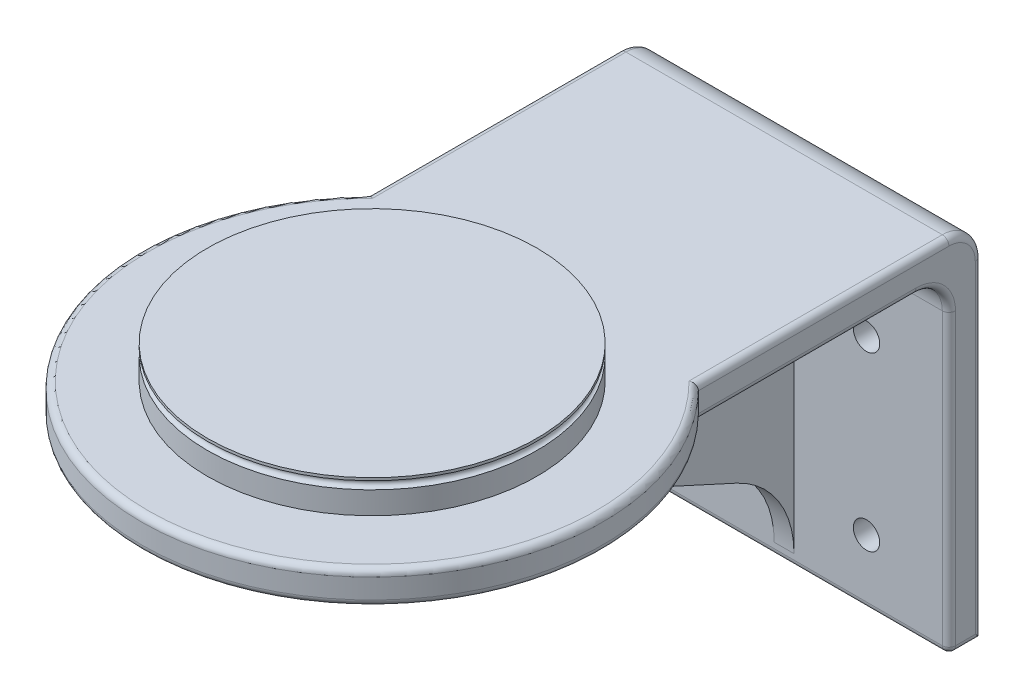
SolidWorks part; units mm, degrees
ref_plane "Front Plane" through (0, 0, 0) normal (0, 0, 1) x (1, 0, 0)
ref_plane "Top Plane" through (0, 0, 0) normal (0, 1, 0) x (1, 0, 0)
ref_plane "Right Plane" through (0, 0, 0) normal (1, 0, 0) x (0, 0, -1)
sketch "Sketch1" plane through (0, 0, 0) normal (1, 0, 0) x (0, 0, -1)
  line L0 (0, 0) -> (-130, 0)
  line L1 (0, 0) -> (0, -50)
  line L2 (-130, 0) -> (-130, 5)
  line L3 (-130, 5) -> (5, 5)
  line L4 (5, 5) -> (5, -50)
  line L5 (5, -50) -> (0, -50)
  dimension "D1" = 130
  dimension "D2" = 50
  dimension "D3" = 5
extrude "Boss-Extrude1" add sketch "Sketch1" along normal blind 50
sketch "Sketch2" plane through (0, 5, 0) normal (0, 1, 0) x (1, 0, 0)
  line L0 (0, 5) -> (50, -130) construction
  circle A0 centre (25, -62.5) radius 25
  dimension "D1" = 50
extrude "Boss-Extrude2" add sketch "Sketch2" along normal blind 5
sketch "Sketch3" plane through (0, 5, 0) normal (0, 1, 0) x (1, 0, 0)
  circle A2 centre (25, -62.5) radius 35
  circle A3 centre (25, -62.5) radius 35
  dimension "D1" = 10
extrude "Boss-Extrude3" add sketch "Sketch3" against normal up to surface (5 mm away) up to face at (25, 0, 65)
ref_plane "Plane1" through (25, 0, 0) normal (1, 0, 0) x (0, 0, -1)
sketch "Sketch4" plane through (25, 0, 0) normal (1, 0, 0) x (0, 0, -1)
  line L0 (-62.5, 10) -> (-62.5, 9) construction
  line L1 (-37.5, 10) -> (-87.5, 10) construction
  line L2 (-62.5, 9) -> (-87.5, 9) construction
  line L3 (-87.5, 10) -> (-87.5, 5) construction
  circle A0 centre (-87.5, 9) radius 0.6
  dimension "D1" = 1.2
  dimension "D2" = 1
sketch "Sketch5" plane through (0, 5, 0) normal (0, 1, 0) x (1, 0, 0)
  line L0 (50, -86.9949) -> (70.537, -86.9949)
  line L1 (70.537, -86.9949) -> (70.537, -135.5769)
  line L2 (70.537, -135.5769) -> (-17.3561, -135.5769)
  line L3 (-17.3561, -135.5769) -> (0, -86.9949)
  line L4 (25, -62.5) -> (25, -87.5) construction
  arc A1 (0, -86.9949) -> (50, -86.9949) centre (25, -62.5) ccw
extrude "Cut-Extrude1" cut sketch "Sketch5" against normal through all
sketch "Sketch7" plane through (25, 0, 0) normal (1, 0, 0) x (0, 0, -1)
  line L0 (0, 0) -> (-84.2622, 0)
  line L1 (-97.5, 0) -> (-38.0051, 0) construction
  line L2 (-84.2622, 0) -> (0, -38.515)
  line L3 (0, 0) -> (0, -50) construction
  line L4 (0, -38.515) -> (0, 0)
extrude "Boss-Extrude5" add sketch "Sketch7" along normal mid plane 3
sketch "Sketch8" plane through (0, 0, 0) normal (0, 0, 1) x (1, 0, 0)
  line L0 (25, -38.515) -> (25, -50) construction
  line L1 (26.5, -38.515) -> (23.5, -38.515) construction
  line L2 (50, -50) -> (0, -50) construction
  line L3 (25, -50) -> (50, -50) construction
  line L4 (25, -50) -> (0, -50) construction
  line L5 (12.5, -50) -> (12.5, 0) construction
  line L6 (23.5, 0) -> (0, 0) construction
  line L7 (37.5, -50) -> (37.5, 0) construction
  line L8 (50, 0) -> (26.5, 0) construction
  circle A0 centre (12.5, -40.2015) radius 2
  circle A1 centre (12.5, -14.0847) radius 2
  circle A2 centre (37.5, -40.2015) radius 2
  circle A3 centre (37.5, -14.0847) radius 2
  dimension "D1" = 4
extrude "Cut-Extrude2" cut sketch "Sketch8" against normal through all
fillet "Fillet1" radius 5 2 edges at (11.75, 0, 0) (38.25, 0, 0)
fillet "Fillet2" radius 5 1 edges at (25, 5, -5)
revolve "Cut-Revolve1" cut sketch "Sketch4" angle 360 about L0
fillet "Fillet3" radius 15 1 edges at (25, -38.515, 0)
fillet "Fillet4" radius 15 1 edges at (25, 0, 84.2622)
fillet "Fillet5" radius 1 1 edges at (25, -50, 0)
fillet "Fillet6" radius 1 18 edges at (50, -25, -5) (50, 3.5355, -3.5355) (0, -25, -5) (0, 3.5355, -3.5355) (0, -50, -3) (0, -49.7071, -0.2929) (0, -27, 0) (0, -1.4645, 1.4645) (50, -50, -3) (50, -49.7071, -0.2929) (50, -27, 0) (50, -1.4645, 1.4645) (50, 5, 19.0026) (0, 5, 19.0026) (25, 5, 97.5) (25, 0, 97.5) (0, 0, 21.5026) (50, 0, 21.5026)
